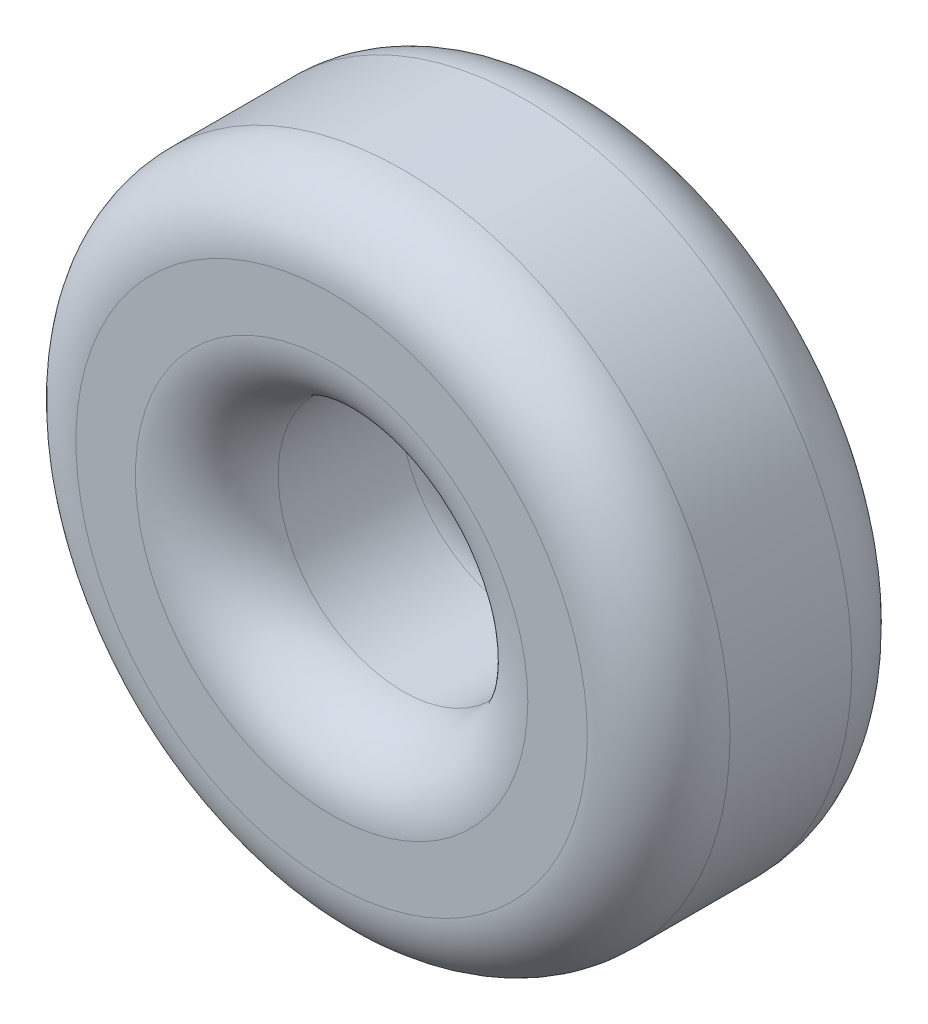
SolidWorks part; units mm, degrees
ref_plane "Front Plane" through (0, 0, 0) normal (0, 0, 1) x (1, 0, 0)
ref_plane "Top Plane" through (0, 0, 0) normal (0, 1, 0) x (1, 0, 0)
ref_plane "Right Plane" through (0, 0, 0) normal (1, 0, 0) x (0, 0, -1)
sketch "Sketch2" plane through (0, 0, 0) normal (0, 0, 1) x (1, 0, 0)
  circle A0 centre (-9.7809, 3.8039) radius 55
  circle A1 centre (-9.7809, 3.8039) radius 21
extrude "Boss-Extrude1" add sketch "Sketch2" along normal blind 44.5
fillet "Fillet1" radius 12 4 edges at (11.2191, 3.8039, 0) (45.2191, 3.8039, 0) (11.2191, 3.8039, 44.5) (45.2191, 3.8039, 44.5)
